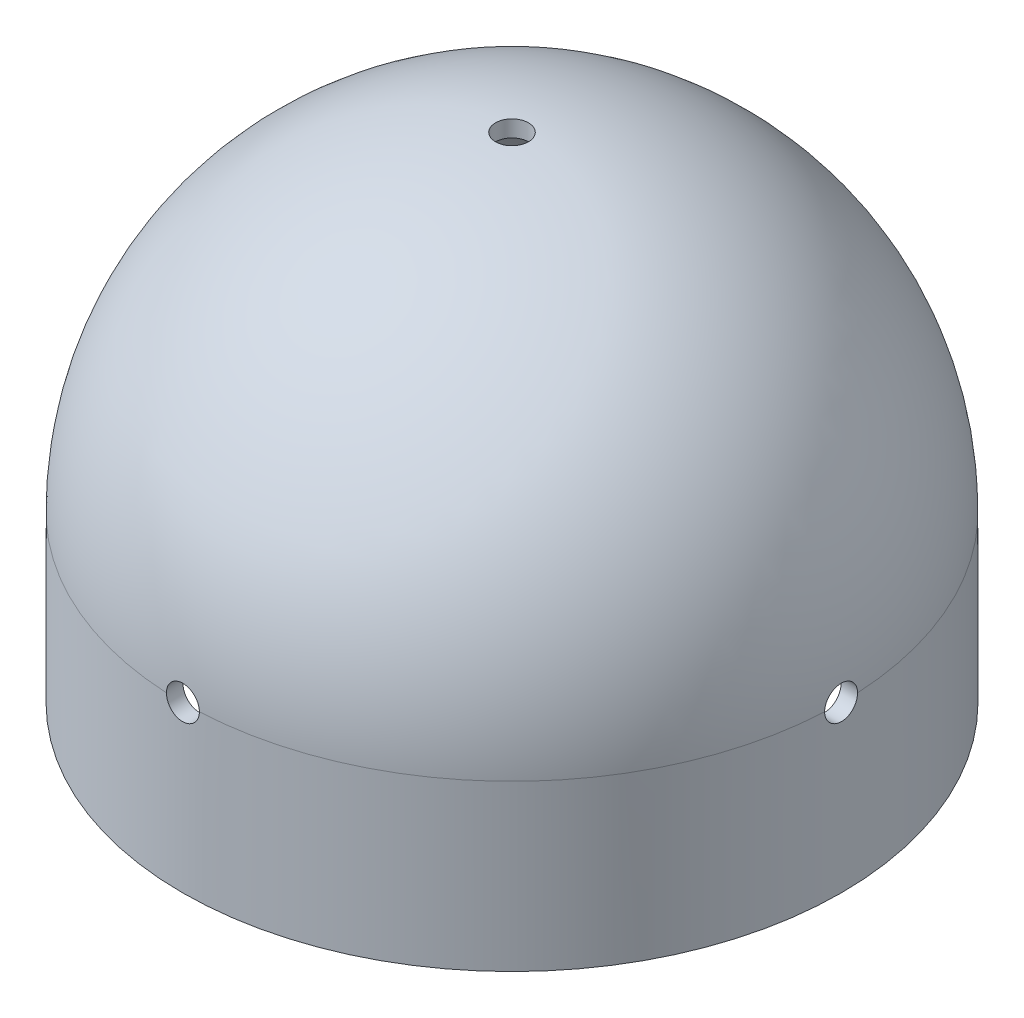
SolidWorks part; units mm, degrees
ref_plane "Front" through (0, 0, 0) normal (0, 0, 1) x (1, 0, 0)
ref_plane "Top" through (0, 0, 0) normal (0, 1, 0) x (1, 0, 0)
ref_plane "Right" through (0, 0, 0) normal (1, 0, 0) x (0, 0, -1)
sketch "Sketch1" plane through (0, 0, 0) normal (0, 0, 1) x (1, 0, 0)
  line L0 (0, 0) -> (0, 15) construction
  line L1 (10, 5) -> (10, 0)
  line L2 (0, 0) -> (12.5069, 0) construction
  line L3 (9.5, 0) -> (9.5, 5)
  line L4 (0, 14.5) -> (0, 15)
  line L5 (9.5, 0) -> (10, 0)
  arc A0 (0, 15) -> (10, 5) centre (0, 5) cw
  arc A1 (9.5, 5) -> (0, 14.5) centre (0, 5) ccw
  dimension "D2" = 10
  dimension "D6" = 9.5
  dimension "D1" = 15
  dimension "D3" = 5
  dimension "D4" = 10
  dimension "D5" = 9.5
revolve "Revolve2" add sketch "Sketch1" angle 360 about L0
sketch "Sketch5" plane through (0, 0, 0) normal (0, 0, 1) x (1, 0, 0)
  line L0 (0, 15.4493) -> (0, -1.172) construction
  circle A0 centre (0, 5) radius 0.5
  dimension "D1" = 1
  dimension "D2" = 5
extrude "Cut-Extrude1" cut sketch "Sketch5" along normal through all
pattern_circular "CirPattern1" count 4 over 360 of "Cut-Extrude1"
sketch "Sketch6" plane through (0, 0, 0) normal (0, 1, 0) x (1, 0, 0)
  circle A0 centre (0, 0) radius 0.5
  dimension "D1" = 1
extrude "Cut-Extrude2" cut sketch "Sketch6" along normal through all
